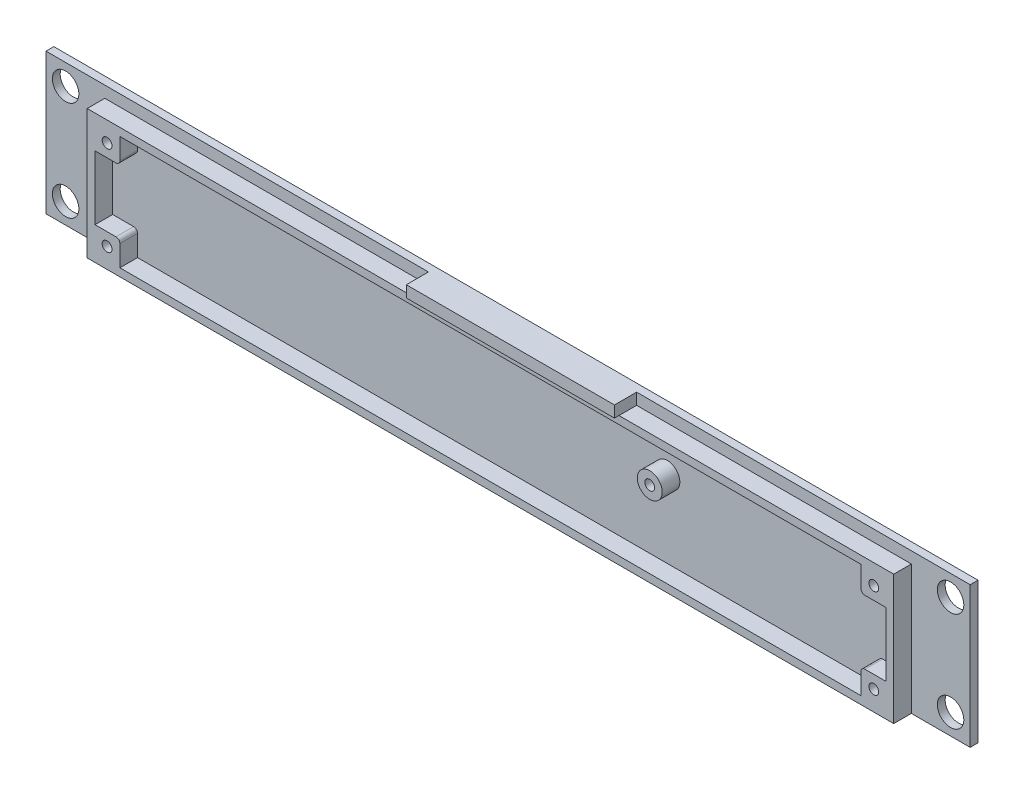
SolidWorks part; units mm, degrees
ref_plane "Front Plane" through (0, 0, 0) normal (0, 0, 1) x (1, 0, 0)
ref_plane "Top Plane" through (0, 0, 0) normal (0, 1, 0) x (1, 0, 0)
ref_plane "Right Plane" through (0, 0, 0) normal (1, 0, 0) x (0, 0, -1)
sketch "Sketch1" plane through (0, 0, 143.1999) normal (0, 0, -1) x (-1, 0, 0)
  line L0 (-178.8717, 101.7132) -> (-178.8717, 130.7332)
  line L1 (-180.8717, 99.7132) -> (24.8683, 99.7132)
  line L2 (-180.8717, 99.7132) -> (-180.8717, 132.7332)
  line L3 (-180.8717, 132.7332) -> (24.8683, 132.7332)
  line L4 (24.8683, 99.7132) -> (24.8683, 132.7332)
  line L5 (-178.8717, 130.7332) -> (22.8683, 130.7332)
  line L6 (22.8683, 101.7132) -> (22.8683, 130.7332)
  line L7 (-178.8717, 101.7132) -> (22.8683, 101.7132)
  line L8 (-57.6917, 133.6532) -> (-57.6917, 123.3132) construction
  line L9 (22.8683, 130.7332) -> (16.5183, 130.7332)
  line L10 (22.8683, 130.7332) -> (22.8683, 124.3832)
  line L11 (22.8683, 124.3832) -> (17.5183, 124.3832)
  line L12 (16.5183, 130.7332) -> (16.5183, 125.3832)
  line L13 (-178.8717, 101.7132) -> (-172.5217, 101.7132)
  line L14 (-178.8717, 101.7132) -> (-178.8717, 108.0632)
  line L15 (-178.8717, 108.0632) -> (-173.5217, 108.0632)
  line L16 (-172.5217, 101.7132) -> (-172.5217, 107.0632)
  line L17 (-178.8717, 130.7332) -> (-172.5217, 130.7332)
  line L18 (-178.8717, 130.7332) -> (-178.8717, 124.3832)
  line L19 (-178.8717, 124.3832) -> (-173.5217, 124.3832)
  line L20 (-172.5217, 130.7332) -> (-172.5217, 125.3832)
  line L21 (22.8683, 101.7132) -> (16.5183, 101.7132)
  line L22 (22.8683, 101.7132) -> (22.8683, 108.0632)
  line L23 (22.8683, 108.0632) -> (17.5183, 108.0632)
  line L24 (16.5183, 101.7132) -> (16.5183, 107.0632)
  line L25 (-110.7917, 132.7332) -> (-57.6917, 132.7332)
  line L26 (-110.7917, 132.7332) -> (-110.7917, 135.8532)
  line L27 (-110.7917, 135.8532) -> (-57.6917, 135.8532)
  line L28 (-57.6917, 132.7332) -> (-57.6917, 135.8532)
  line L29 (-110.7917, 123.3132) -> (-110.7917, 133.6532) construction
  line L30 (-58.6917, 135.8532) -> (-109.7917, 135.8532) construction
  arc A0 (-173.5217, 124.3832) -> (-172.5217, 125.3832) centre (-173.5217, 125.3832) ccw
  arc A1 (-173.5217, 108.0632) -> (-172.5217, 107.0632) centre (-173.5217, 107.0632) cw
  arc A2 (17.5183, 124.3832) -> (16.5183, 125.3832) centre (17.5183, 125.3832) cw
  arc A3 (16.5183, 107.0632) -> (17.5183, 108.0632) centre (17.5183, 107.0632) cw
  circle A4 centre (-118.6417, 121.3032) radius 3.175
  point P26 (-172.5217, 108.0632)
  point P29 (16.5183, 124.3832)
  dimension "D6" = 1
  dimension "D7" = 6.35
  dimension "D2" = 6.35
  dimension "D3" = 6.35
  dimension "D4" = 6.35
  dimension "D5" = 6.35
  dimension "D8" = 0
  dimension "D9" = 0
  dimension "D10" = 0
  dimension "D1" = 2
extrude "Boss-Extrude1" add sketch "Sketch1" along normal blind 4.5 contours L1 L4 L3 L2 L7 L0 L5 L6 | A3 L24 L7 L6 L23 | A2 L11 L6 L5 L12 | A4 | L19 A0 L20 L5 L0 | A1 L15 L0 L7 L16
hole_wizard "Tap Drill for M3x0.5 Tap1" positions "Sketch3" profile "Sketch4" hole size "M3x0.5" standard "ANSI Metric" end condition through all
sketch "Sketch3" plane through (0, 0, 143.1999) normal (0, 0, 1) x (1, 0, 0)
  point P0 (-19.7883, 127.6532)
  point P3 (-19.7883, 104.7932)
  point P6 (118.6417, 121.3032)
  point P9 (175.7917, 127.6532)
  point P12 (175.7917, 104.7932)
sketch "Sketch4" plane through (-19.7883, 127.6532, 143.1999) normal (1, 0, 0) x (0, -1, 0)
  line L0 (0, 0) -> (0, 4.5)
  line L1 (0, 4.5) -> (1.25, 4.5)
  line L2 (1.25, 4.5) -> (1.25, 0)
  line L5 (1.25, 0) -> (0, 0)
  line L11 (0, -6.35) -> (0, 107.95) construction
  dimension "Thru Hole Dia." = 2.5
  dimension "Thru Hole Depth" = 4.5
sketch "Sketch5" plane through (0, 0, 138.6999) normal (0, 0, -1) x (-1, 0, 0)
  line L0 (-180.8717, 99.7132) -> (-180.8717, 132.7332) construction
  line L1 (-195.8717, 135.6532) -> (39.8683, 135.6532)
  line L2 (-195.8717, 135.6532) -> (-195.8717, 99.7132)
  line L3 (-195.8717, 99.7132) -> (39.8683, 99.7132)
  line L4 (39.8683, 135.6532) -> (39.8683, 99.7132)
  line L5 (24.8683, 99.7132) -> (24.8683, 132.7332) construction
  line L6 (-109.7917, 135.6532) -> (-58.6917, 135.6532) construction
  dimension "D1" = 15
  dimension "D2" = 15
  dimension "D3" = 0
extrude "Boss-Extrude2" add sketch "Sketch5" along normal blind 2
sketch "Sketch6" plane through (0, 0, 138.6999) normal (0, 0, 1) x (1, 0, 0)
  line L0 (-39.8683, 135.6532) -> (195.8717, 135.6532) construction
  line L1 (110.7917, 135.6532) -> (57.6917, 135.6532)
  line L2 (110.7917, 135.6532) -> (110.7917, 132.7332)
  line L3 (110.7917, 132.7332) -> (57.6917, 132.7332)
  line L4 (57.6917, 135.6532) -> (57.6917, 132.7332)
  line L5 (180.8717, 132.7332) -> (-24.8683, 132.7332) construction
  line L6 (57.6917, 133.6532) -> (57.6917, 123.3132) construction
  line L7 (110.7917, 123.3132) -> (110.7917, 133.6532) construction
  dimension "D1" = 0
  dimension "D2" = 0
extrude "Boss-Extrude3" add sketch "Sketch6" along normal offset from surface (5.65 mm away) 0.5
sketch "Sketch7" plane through (0, 0, 138.6999) normal (0, 0, 1) x (1, 0, 0)
  line L0 (-34.8683, 130.3832) -> (-34.8683, 104.9832)
  line L1 (-39.8683, 99.7132) -> (-39.8683, 135.6532) construction
  line L2 (190.8717, 130.3832) -> (190.8717, 104.9832)
  line L3 (195.8717, 135.6532) -> (195.8717, 99.7132) construction
  point P4 (190.8717, 117.6832)
  point P5 (195.8717, 117.6832)
  point P9 (-34.8683, 117.6832)
  dimension "D1" = 25.4
  dimension "D2" = 0
  dimension "D3" = 5
  dimension "D4" = 5
hole_wizard "1/4 Clearance Hole1" positions "Sketch8" profile "Sketch9" hole size "1/4" standard "ANSI Inch" end condition through all
sketch "Sketch8" plane through (0, 0, 138.6999) normal (0, 0, 1) x (1, 0, 0)
  point P0 (190.8717, 104.9832)
  point P3 (190.8717, 130.3832)
  point P6 (-34.8683, 104.9832)
  point P9 (-34.8683, 130.3832)
sketch "Sketch9" plane through (190.8717, 104.9832, 138.6999) normal (1, 0, 0) x (0, -1, 0)
  line L0 (0, 0) -> (0, 2)
  line L1 (0, 2) -> (3.3782, 2)
  line L2 (3.3782, 2) -> (3.3782, 0)
  line L5 (3.3782, 0) -> (0, 0)
  line L11 (0, -6.35) -> (0, 107.95) construction
  dimension "Thru Hole Dia." = 6.7564
  dimension "Thru Hole Depth" = 2
